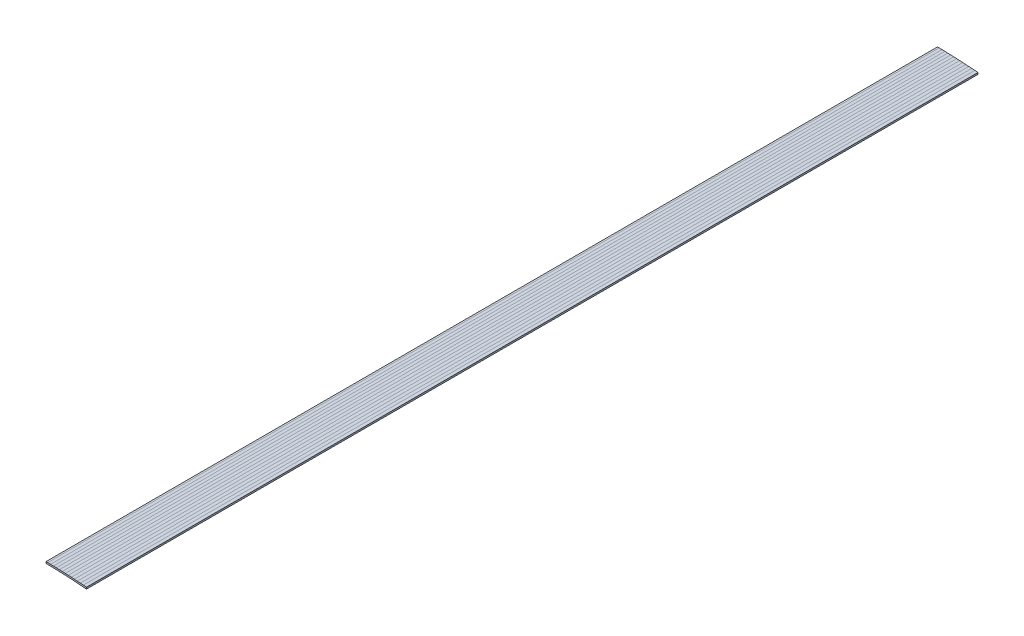
SolidWorks part; units mm, degrees
material "BLADE_CFRP_1550_PROVISIONAL"
ref_plane "Front Plane" through (0, 0, 0) normal (0, 0, 1) x (1, 0, 0)
ref_plane "Top Plane" through (0, 0, 0) normal (0, 1, 0) x (1, 0, 0)
ref_plane "Right Plane" through (0, 0, 0) normal (1, 0, 0) x (0, 0, -1)
sketch "Sketch1" plane through (0, 0, 0) normal (0, 0, 1) x (1, 0, 0)
  line L0 (12.4209, 2.0246) -> (13.124, 2.0139)
  line L1 (13.124, 2.0139) -> (13.8363, 1.998)
  line L2 (13.8363, 1.998) -> (14.5566, 1.9773)
  line L3 (14.5566, 1.9773) -> (15.2838, 1.9518)
  line L4 (15.2838, 1.9518) -> (16.0169, 1.9219)
  line L5 (16.0169, 1.9219) -> (16.7546, 1.8877)
  line L6 (16.7546, 1.8877) -> (17.4958, 1.8495)
  line L7 (17.4958, 1.8495) -> (18.2394, 1.8076)
  line L8 (18.2394, 1.8076) -> (18.9843, 1.7622)
  line L9 (18.9843, 1.7622) -> (19.7292, 1.7136)
  line L10 (19.7292, 1.7136) -> (20.473, 1.6621)
  line L11 (20.473, 1.6621) -> (21.2145, 1.6079)
  line L12 (21.2145, 1.6079) -> (21.9527, 1.5513)
  line L13 (21.9527, 1.5513) -> (22, 1.5475)
  line L14 (22, 1.5475) -> (22, 1.1462)
  line L15 (22, 1.1462) -> (21.9215, 1.1525)
  line L16 (21.9215, 1.1525) -> (21.1847, 1.209)
  line L17 (21.1847, 1.209) -> (20.4446, 1.2631)
  line L18 (20.4446, 1.2631) -> (19.7023, 1.3145)
  line L19 (19.7023, 1.3145) -> (18.9591, 1.363)
  line L20 (18.9591, 1.363) -> (18.216, 1.4083)
  line L21 (18.216, 1.4083) -> (17.4743, 1.4501)
  line L22 (17.4743, 1.4501) -> (16.735, 1.4882)
  line L23 (16.735, 1.4882) -> (15.9994, 1.5222)
  line L24 (15.9994, 1.5222) -> (15.2686, 1.5521)
  line L25 (15.2686, 1.5521) -> (14.5438, 1.5775)
  line L26 (14.5438, 1.5775) -> (13.826, 1.5982)
  line L27 (13.826, 1.5982) -> (13.1165, 1.6139)
  line L28 (13.1165, 1.6139) -> (12.4163, 1.6246)
  line L29 (12.4163, 1.6246) -> (12, 1.6279)
  line L30 (12, 1.6279) -> (12, 2.0279)
  line L31 (12, 2.0279) -> (12.4209, 2.0246)
extrude "Defined_Material_Section_L220" add sketch "Sketch1" along normal blind 220
